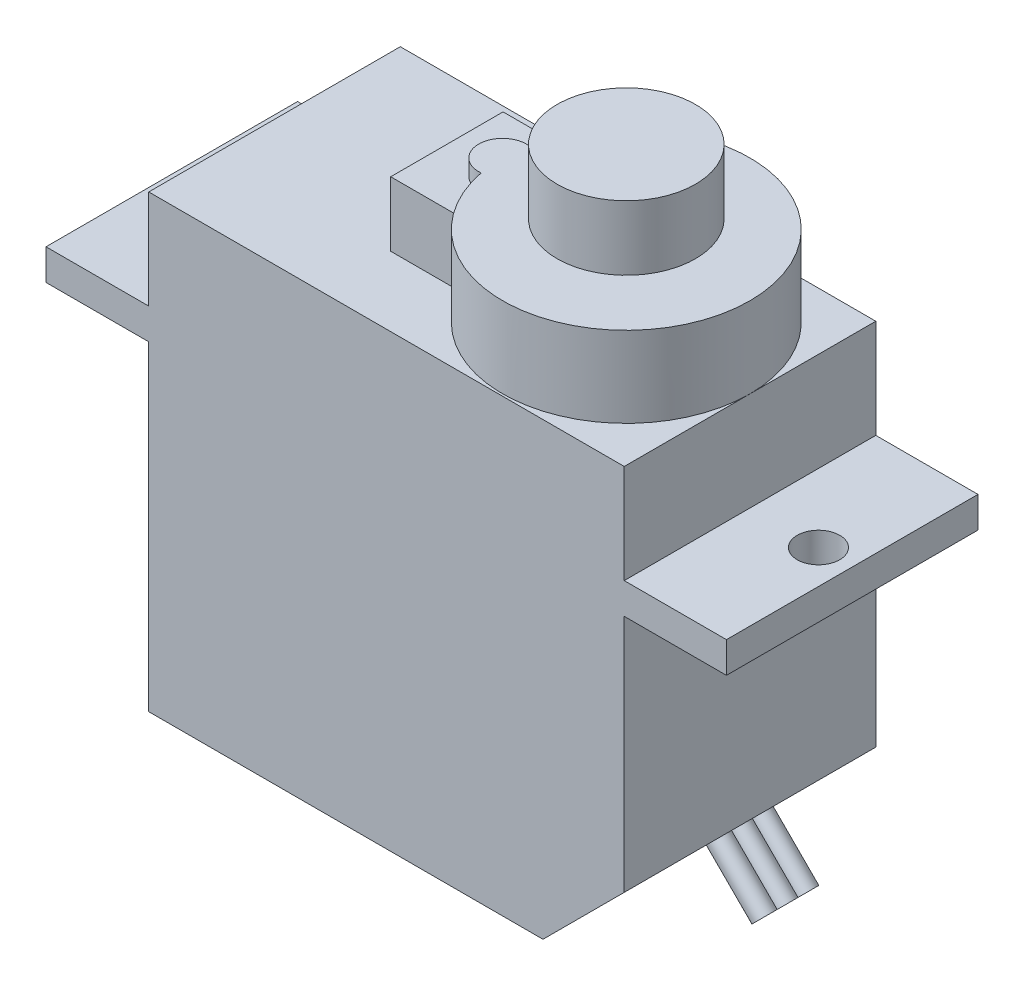
SolidWorks part; units mm, degrees
ref_plane "Front Plane" through (0, 0, 0) normal (0, 0, 1) x (1, 0, 0)
ref_plane "Top Plane" through (0, 0, 0) normal (0, 1, 0) x (1, 0, 0)
ref_plane "Right Plane" through (0, 0, 0) normal (1, 0, 0) x (0, 0, -1)
sketch "Sketch1" plane through (0, 0, 0) normal (0, 0, 1) x (1, 0, 0)
  line L0 (19.12, 0) -> (23.06, 3.94)
  line L1 (0, 0) -> (19.12, 0)
  line L2 (0, 0) -> (0, 21.83)
  line L3 (0, 21.83) -> (23.06, 21.83)
  line L4 (23.06, 3.94) -> (23.06, 21.83)
  point P3 (23.06, 0)
  dimension "D1" = 3.94
  dimension "D2" = 45
extrude "Boss-Extrude1" add sketch "Sketch1" against normal blind 12.2
sketch "Sketch4" plane through (0, 0, 0) normal (0, 0, 1) x (1, 0, 0)
  line L1 (-4.9829, 15.5353) -> (28.0171, 15.5353)
  line L2 (-4.9829, 15.5353) -> (-4.9829, 17.0353)
  line L3 (-4.9829, 17.0353) -> (28.0171, 17.0353)
  line L4 (28.0171, 15.5353) -> (28.0171, 17.0353)
extrude "Boss-Extrude2" add sketch "Sketch4" against normal blind 12.2 separate body
ref_plane "Plane1" through (0, 17, 0) normal (0, 1, 0) x (1, 0, 0)
sketch "Sketch6" plane through (0, 17, 0) normal (0, 1, 0) x (1, 0, 0)
  circle A0 centre (-3.31, 6.1) radius 1.03
extrude "Cut-Extrude1" cut sketch "Sketch6" against normal through all both and the other way through all
sketch "Sketch7" plane through (0, 17, 0) normal (0, 1, 0) x (1, 0, 0)
  circle A0 centre (26.38, 6.1) radius 1.03
extrude "Cut-Extrude2" cut sketch "Sketch7" against normal through all both and the other way through all
sketch "Sketch9" plane through (0, 17, 0) normal (0, 1, 0) x (1, 0, 0)
  circle A0 centre (17.06, 6.1) radius 6
extrude "Boss-Extrude3" add sketch "Sketch9" along normal blind 8.74
sketch "Sketch11" plane through (0, 17, 0) normal (0, 1, 0) x (1, 0, 0)
  circle A0 centre (11.06, 6.1) radius 1.16
  circle A1 centre (17.06, 6.1) radius 6 construction
  circle A2 centre (17.06, 6.1) radius 6 construction
extrude "Boss-Extrude4" add sketch "Sketch11" along normal blind 8.74
sketch "Sketch13" plane through (0, 17, 0) normal (0, 1, 0) x (1, 0, 0)
  line L1 (13.76, 3.375) -> (8.36, 3.375)
  line L2 (13.76, 3.375) -> (13.76, 8.825)
  line L3 (13.76, 8.825) -> (8.36, 8.825)
  line L4 (8.36, 3.375) -> (8.36, 8.825)
  line L5 (13.76, 3.375) -> (8.36, 8.825) construction
  line L6 (13.76, 8.825) -> (8.36, 3.375) construction
  point P0 (11.06, 6.1)
extrude "Boss-Extrude5" add sketch "Sketch13" along normal blind 7.96
sketch "Sketch14" plane through (0, 17, 0) normal (0, 1, 0) x (1, 0, 0)
  circle A0 centre (17.06, 6.1) radius 2.345
extrude "Boss-Extrude6" add sketch "Sketch14" along normal blind 11.51
ref_plane "Plane2" through (0, 28.51, 0) normal (0, 1, 0) x (1, 0, 0)
sketch "Sketch15" plane through (0, 28.51, 0) normal (0, 1, 0) x (1, 0, 0)
  circle A0 centre (17.06, 6.1) radius 0.635
extrude "Cut-Extrude3" cut sketch "Sketch15" against normal blind 3.13
sketch "Sketch17" plane through (0, 28.51, 0) normal (0, 1, 0) x (1, 0, 0)
  circle A0 centre (17.06, 6.1) radius 3.355
extrude "Boss-Extrude7" add sketch "Sketch17" against normal blind 3.13 from offset 0.8
sketch "Sketch18" plane through (9.56, -9.56, 0) normal (0.7071, -0.7071, 0) x (0, 0, -1)
  line L0 (6.1, 19.0919) -> (6.1, 13.5199) construction
  line L1 (12.2, 19.0919) -> (0, 19.0919) construction
  line L2 (12.2, 13.5199) -> (0, 13.5199) construction
  circle A1 centre (5.09, 18.387) radius 0.5
  circle A2 centre (6.1, 18.387) radius 0.5
  circle A3 centre (7.11, 18.387) radius 0.5
extrude "Boss-Extrude8" add sketch "Sketch18" along normal blind 3.13
